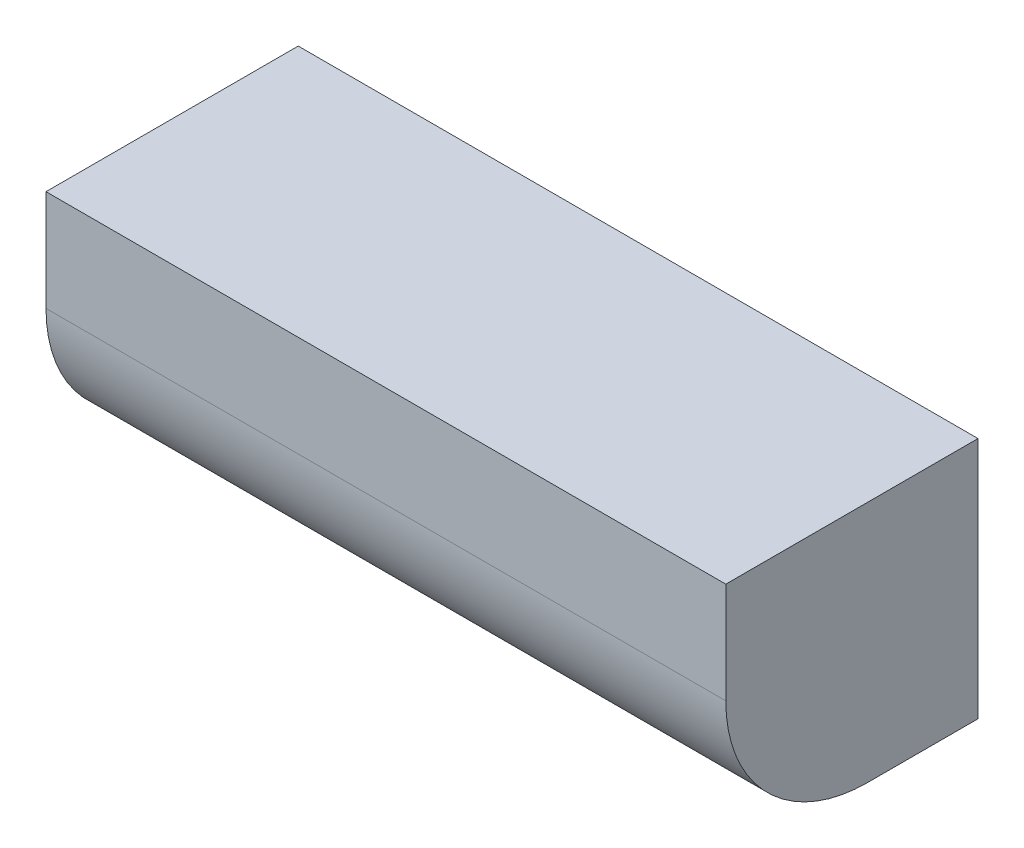
SolidWorks part; units mm, degrees
ref_plane "Front Plane" through (0, 0, 0) normal (0, 0, 1) x (1, 0, 0)
ref_plane "Top Plane" through (0, 0, 0) normal (0, 1, 0) x (1, 0, 0)
ref_plane "Right Plane" through (0, 0, 0) normal (1, 0, 0) x (0, 0, -1)
sketch "Sketch1" plane through (0, 0, 0) normal (0, 0, 1) x (1, 0, 0)
  line L1 (0, 0) -> (48, 0)
  line L2 (0, 0) -> (0, 53)
  line L3 (0, 53) -> (48, 53)
  line L4 (48, 0) -> (48, 53)
  dimension "D1" = 53
  dimension "D2" = 48
extrude "Boss-Extrude1" add sketch "Sketch1" along normal blind 10
sketch "Sketch2" plane through (0, 0, 0) normal (0, 0, -1) x (-1, 0, 0)
  line L0 (0, 53) -> (0, 0) construction
  line L1 (-48, 0) -> (0, 0)
  line L2 (-48, 0) -> (-48, -5.6163)
  line L3 (-48, -5.6163) -> (0, -5.6163)
  line L4 (0, 0) -> (0, -5.6163)
  dimension "D1" = 5.6163
extrude "Boss-Extrude2" add sketch "Sketch2" against normal blind 33.1918
sketch "Sketch4" plane through (0, 0, 10) normal (0, 0, 1) x (1, 0, 0)
  line L1 (0, 53) -> (4, 53)
  line L2 (0, 53) -> (0, 43)
  line L3 (0, 43) -> (4, 43)
  line L4 (4, 53) -> (4, 43)
  line L5 (48, 53) -> (44, 53)
  line L6 (48, 53) -> (48, 43)
  line L7 (48, 43) -> (44, 43)
  line L8 (44, 53) -> (44, 43)
  dimension "D1" = 10
  dimension "D2" = 4
extrude "Boss-Extrude4" add sketch "Sketch4" along normal blind 40
sketch "Sketch5" plane through (0, 0, 10) normal (0, 0, 1) x (1, 0, 0)
  line L0 (48, 0) -> (48, 43) construction
  line L1 (0, 0) -> (48, 0)
  line L2 (0, 0) -> (0, 10.8609)
  line L3 (0, 10.8609) -> (48, 10.8609)
  line L4 (48, 0) -> (48, 10.8609)
  dimension "D1" = 10.8609
extrude "Boss-Extrude5" add sketch "Sketch5" along normal up to surface (23.1918 mm away) up to face at (24, -2.8082, 33.1918)
sketch "Sketch6" plane through (0, -5.6163, 0) normal (0, -1, 0) x (1, 0, 0)
  line L0 (0, 0) -> (0, 28.1918) construction
  line L1 (0, 33.1918) -> (0, 0) construction
  line L2 (48, 33.1918) -> (48, 0) construction
  line L3 (0, 28.1918) -> (48, 28.1918)
  line L4 (0, 28.1918) -> (0, 33.1918)
  line L5 (0, 33.1918) -> (48, 33.1918)
  line L6 (48, 28.1918) -> (48, 33.1918)
  line L8 (48, 33.1918) -> (0, 33.1918) construction
  dimension "D2" = 5
extrude "Boss-Extrude6" add sketch "Sketch6" along normal blind 42.3
sketch "Sketch7" plane through (0, 0, 0) normal (-1, 0, 0) x (0, 0, 1)
  line L0 (33.1918, 10.8609) -> (10, 10.8609) construction
  line L1 (0, -5.6163) -> (-12.8082, -5.6163)
  line L2 (0, -5.6163) -> (0, 10.8609)
  line L3 (0, 10.8609) -> (-12.8082, 10.8609)
  line L4 (-12.8082, -5.6163) -> (-12.8082, 10.8609)
  line L5 (28.1918, -47.9163) -> (28.1918, -5.6163) construction
  dimension "D1" = 41
extrude "Boss-Extrude7" add sketch "Sketch7" against normal up to surface (48 mm away) up to face at (48, 10.6657, 24.2767)
sketch "Sketch8" plane through (0, 0, 28.1918) normal (0, 0, -1) x (-1, 0, 0)
  line L0 (-24, -26.6163) -> (-24, -5.6163) construction
  line L1 (0, -5.6163) -> (-48, -5.6163) construction
  line L3 (-8.5, -42.1163) -> (-39.5, -42.1163) construction
  line L4 (-8.5, -42.1163) -> (-8.5, -11.1163) construction
  line L5 (-8.5, -11.1163) -> (-39.5, -11.1163) construction
  line L6 (-39.5, -42.1163) -> (-39.5, -11.1163) construction
  line L7 (-8.5, -42.1163) -> (-39.5, -11.1163) construction
  line L8 (-8.5, -11.1163) -> (-39.5, -42.1163) construction
  circle A0 centre (-24, -26.6163) radius 11.5
  circle A1 centre (-39.5, -11.1163) radius 2
  circle A2 centre (-39.5, -42.1163) radius 2
  circle A3 centre (-8.5, -11.1163) radius 2
  circle A4 centre (-8.5, -42.1163) radius 2
  dimension "D2" = 23
  dimension "D4" = 4
  dimension "D1" = 21
  dimension "D3" = 31
extrude "Cut-Extrude1" cut sketch "Sketch8" against normal up to next
fillet "Fillet1" radius 10 1 edges at (24, 10.8609, 0)
fillet "Fillet2" radius 4 2 edges at (2, 43, 10) (46, 43, 10)
sketch "Sketch9" plane through (48, 0, 0) normal (1, 0, 0) x (0, 0, -1)
  line L1 (12.8082, 10.8609) -> (17.8082, 10.8609)
  line L2 (12.8082, 10.8609) -> (12.8082, -5.6163)
  line L3 (12.8082, -5.6163) -> (17.8082, -5.6163)
  line L4 (17.8082, 10.8609) -> (17.8082, -5.6163)
  line L5 (-28.1918, -5.6163) -> (12.8082, -5.6163) construction
  dimension "D1" = 5
extrude "Boss-Extrude9" add sketch "Sketch9" against normal up to surface (48 mm away) contours L4 L3 L2 L1 up to face at (0, 13.3569, 15.8852)
sketch "Sketch10" plane through (0, 0, 10) normal (0, 0, 1) x (1, 0, 0)
  line L0 (4, 53) -> (9, 35) construction
  line L1 (9, 35) -> (39, 35) construction
  line L2 (39, 35) -> (44, 53) construction
  line L3 (44, 53) -> (4, 53) construction
  line L4 (44, 53) -> (44, 43) construction
  line L6 (12.429, 36.9797) -> (9, 38.9595)
  line L7 (9, 38.9595) -> (5.571, 36.9797)
  line L8 (5.571, 36.9797) -> (5.571, 33.0203)
  line L9 (5.571, 33.0203) -> (9, 31.0405)
  line L10 (9, 31.0405) -> (12.429, 33.0203)
  line L11 (12.429, 33.0203) -> (12.429, 36.9797)
  line L12 (35.571, 36.9797) -> (35.571, 33.0203)
  line L13 (35.571, 33.0203) -> (39, 31.0405)
  line L14 (39, 31.0405) -> (42.429, 33.0203)
  line L15 (42.429, 33.0203) -> (42.429, 36.9797)
  line L16 (42.429, 36.9797) -> (39, 38.9595)
  line L17 (39, 38.9595) -> (35.571, 36.9797)
  circle A0 centre (9, 35) radius 3.429 construction
  circle A1 centre (39, 35) radius 3.429 construction
  dimension "D1" = 6.858
  dimension "D2" = 30
  dimension "D3" = 18
extrude "Cut-Extrude2" cut sketch "Sketch10" against normal blind 6
sketch "Sketch11" plane through (0, 0, 4) normal (0, 0, 1) x (1, 0, 0)
  circle A0 centre (9, 35) radius 1.9304
  circle A1 centre (39, 35) radius 1.9304
  dimension "D1" = 3.8608
extrude "Cut-Extrude3" cut sketch "Sketch11" against normal blind 6
sketch "Sketch12" plane through (0, 53, 0) normal (0, 1, 0) x (1, 0, 0)
  line L0 (0, 0) -> (0, -50)
  line L1 (0, -50) -> (4, -50)
  line L2 (4, -50) -> (4, -10)
  line L3 (4, -10) -> (44, -10)
  line L4 (44, -10) -> (44, -50)
  line L5 (44, -50) -> (48, -50)
  line L6 (48, -50) -> (48, 0)
  line L7 (48, 0) -> (0, 0)
extrude "Boss-Extrude11" add sketch "Sketch12" along normal blind 3
sketch "Sketch13" plane through (48, 0, 0) normal (1, 0, 0) x (0, 0, -1)
  line L0 (0, 56) -> (0, 20.8609) construction
  line L1 (17.8082, 10.8609) -> (10, 10.8609)
  line L2 (17.8082, 10.8609) -> (17.8082, 28)
  line L3 (17.8082, 28) -> (0, 28)
  line L4 (0, 20.8609) -> (0, 28)
  arc A0 (0, 20.8609) -> (10, 10.8609) centre (10, 20.8609) ccw
  arc A1 (0, 20.8609) -> (10, 10.8609) centre (10, 20.8609) ccw construction
  dimension "D1" = 17.1391
extrude "Boss-Extrude12" add sketch "Sketch13" against normal up to surface (48 mm away) up to face at (0, 13.7855, 15.171)
sketch "Sketch14" plane through (48, 0, 0) normal (1, 0, 0) x (0, 0, -1)
  line L0 (0, 28) -> (0, 20.8609)
  line L1 (17.8082, 10.8609) -> (10, 10.8609)
  line L2 (0, 28) -> (17.8082, 28)
  line L3 (17.8082, 28) -> (17.8082, 10.8609)
  line L5 (-76.8161, -52.9018) -> (43.0088, -52.9018)
  line L6 (-76.8161, -52.9018) -> (-76.8161, 69.3357)
  line L7 (-76.8161, 69.3357) -> (43.0088, 69.3357)
  line L8 (43.0088, -52.9018) -> (43.0088, 69.3357)
  arc A0 (0, 20.8609) -> (10, 10.8609) centre (10, 20.8609) ccw
  arc A1 (0, 20.8609) -> (10, 10.8609) centre (10, 20.8609) ccw construction
extrude "Cut-Extrude4" cut sketch "Sketch14" against normal through all
